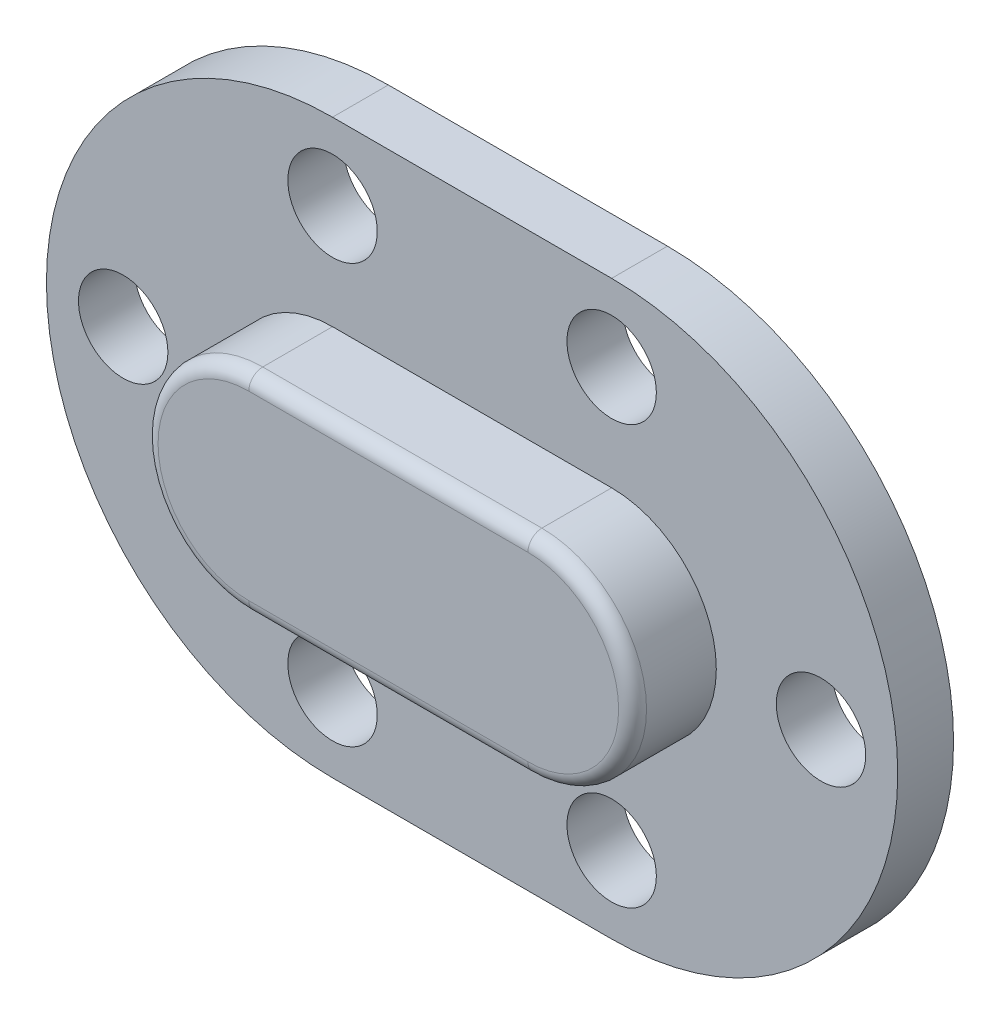
SolidWorks part; units mm, degrees
ref_plane "前视基准面" through (0, 0, 0) normal (0, 0, 1) x (1, 0, 0)
ref_plane "上视基准面" through (0, 0, 0) normal (0, 1, 0) x (1, 0, 0)
ref_plane "右视基准面" through (0, 0, 0) normal (1, 0, 0) x (0, 0, -1)
sketch "草图1" plane through (0, 0, 0) normal (0, 0, 1) x (1, 0, 0)
  line L0 (-10, 0) -> (10, 0) construction
  line L1 (-10, 20.5) -> (10, 20.5)
  line L2 (-10, -20.5) -> (10, -20.5)
  arc A0 (-10, 20.5) -> (-10, -20.5) centre (-10, 0) ccw
  arc A1 (10, -20.5) -> (10, 20.5) centre (10, 0) ccw
  point P2 (0, 0)
  dimension "D2" = 20
  dimension "D1" = 41
extrude "凸台-拉伸1" add sketch "草图1" along normal blind 4
sketch "草图2" plane through (0, 0, 4) normal (0, 0, 1) x (1, 0, 0)
  line L0 (-10, 0) -> (10, 0) construction
  line L1 (-10, 7.5) -> (10, 7.5)
  line L2 (-10, -7.5) -> (10, -7.5)
  arc A0 (-10, 7.5) -> (-10, -7.5) centre (-10, 0) ccw
  arc A1 (10, -7.5) -> (10, 7.5) centre (10, 0) ccw
  point P2 (0, 0)
  dimension "D1" = 20
  dimension "D2" = 15
extrude "凸台-拉伸2" add sketch "草图2" along normal blind 6
hole_wizard "Ø8.0 (8) 直径孔1" positions "草图8" profile "草图9" hole size "Ø8.0" standard "GB"
sketch "草图8" plane through (0, 0, 0) normal (0, 0, -1) x (-1, 0, 0)
  line L0 (-10, 0) -> (10, 0)
  point P0 (-10, 0)
  point P2 (10, 0)
  dimension "D1" = 20
sketch "草图9" plane through (10, 0, 0) normal (1, 0, 0) x (0, 1, 0)
  line L0 (0, 0) -> (0, 9.4034)
  line L1 (0, 9.4034) -> (4, 7)
  line L2 (4, 7) -> (4, 0)
  line L5 (4, 0) -> (0, 0)
  line L10 (0, 9.4034) -> (-4, 7) construction
  line L11 (0, -6.35) -> (0, 107.95) construction
  dimension "孔直径" = 8
  dimension "孔深度" = 7
  dimension "导头角度" = 118
fillet "圆角2" radius 1 4 edges at (0, 7.5, 10) (17.5, 0, 10) (0, -7.5, 10) (-17.5, 0, 10)
sketch "草图10" plane through (0, 0, 4) normal (0, 0, 1) x (1, 0, 0)
  line L0 (0, 0) -> (-10, 0)
  line L1 (-10, 0) -> (-10, 15)
  circle A0 centre (-10, 15) radius 3.2035
  point P5 (-10.2649, 15)
  dimension "D1" = 10
  dimension "D2" = 15
extrude "切除-拉伸1" cut sketch "草图10" against normal through all both and the other way through all
pattern_circular "阵列(圆周)1" count 3 over 180 about axis through (-10, 0, 0) along (0, 0, 1) of "切除-拉伸1"
mirror "镜向1" about plane through (0, 0, 0) normal (1, 0, 0) of "阵列(圆周)1", "切除-拉伸1"
